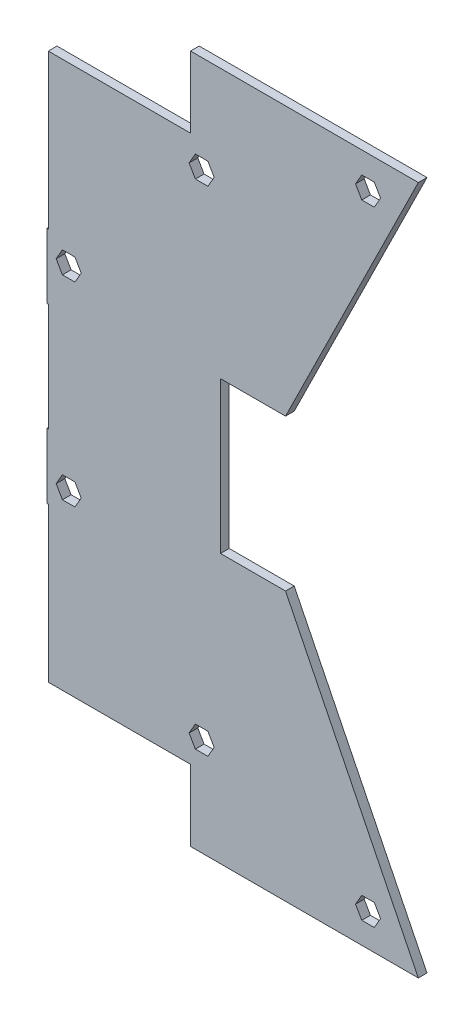
SolidWorks part; units mm, degrees
ref_plane "Front Plane" through (0, 0, 0) normal (0, 0, 1) x (1, 0, 0)
ref_plane "Top Plane" through (0, 0, 0) normal (0, 1, 0) x (1, 0, 0)
ref_plane "Right Plane" through (0, 0, 0) normal (1, 0, 0) x (0, 0, -1)
sketch "Sketch1" plane through (0, 0, 0) normal (0, 0, 1) x (1, 0, 0)
  line L0 (-2.9301, -104.5098) -> (-3.3149, -104.5098)
  line L1 (-3.3149, -72.8868) -> (-2.9301, -72.8868)
  line L54 (4.8681, -57.0118) -> (6.7012, -60.1868)
  line L55 (6.7012, -60.1868) -> (4.8681, -63.3618)
  line L56 (4.8681, -63.3618) -> (1.202, -63.3618)
  line L57 (1.202, -63.3618) -> (-0.6311, -60.1868)
  line L58 (-0.6311, -60.1868) -> (1.202, -57.0118)
  line L59 (1.202, -57.0118) -> (4.8681, -57.0118)
  line L60 (45.6227, -160.9613) -> (43.7896, -157.7863)
  line L61 (43.7896, -164.1363) -> (45.6227, -160.9613)
  line L62 (40.1235, -164.1363) -> (43.7896, -164.1363)
  line L63 (38.2904, -160.9613) -> (40.1235, -164.1363)
  line L64 (40.1235, -157.7863) -> (38.2904, -160.9613)
  line L65 (43.7896, -157.7863) -> (40.1235, -157.7863)
  line L66 (92.507, -183.1863) -> (88.8408, -183.1863)
  line L67 (92.507, -183.1863) -> (94.3401, -180.0113)
  line L68 (94.3401, -180.0113) -> (92.507, -176.8363)
  line L69 (92.507, -176.8363) -> (88.8408, -176.8363)
  line L70 (87.0077, -180.0113) -> (88.8408, -183.1863)
  line L71 (88.8408, -176.8363) -> (87.0077, -180.0113)
  line L72 (88.8408, -0.5603) -> (87.0077, 2.6147)
  line L73 (92.507, -0.5603) -> (88.8408, -0.5603)
  line L74 (94.3401, 2.6147) -> (92.507, -0.5603)
  line L75 (92.507, 5.7897) -> (94.3401, 2.6147)
  line L76 (92.507, 5.7897) -> (88.8408, 5.7897)
  line L77 (87.0077, 2.6147) -> (88.8408, 5.7897)
  line L78 (47.4851, -66.5368) -> (47.4851, -72.8868)
  line L79 (47.4851, -104.5098) -> (47.4851, -110.8598)
  line L80 (66.5174, -66.5368) -> (105.3971, 12.1397)
  line L81 (105.3971, 12.1397) -> (38.7094, 12.1397)
  line L82 (43.7896, -13.2603) -> (45.6227, -16.4353)
  line L83 (45.6227, -16.4353) -> (43.7896, -19.6103)
  line L84 (43.7896, -19.6103) -> (40.1235, -19.6103)
  line L85 (38.2904, -16.4353) -> (40.1235, -13.2603)
  line L86 (40.1235, -19.6103) -> (38.2904, -16.4353)
  line L87 (40.1235, -13.2603) -> (43.7896, -13.2603)
  line L88 (38.7094, 12.1397) -> (38.7094, -8.6883)
  line L89 (-2.9301, -8.6883) -> (38.7094, -8.6883)
  line L90 (-3.3149, -53.8368) -> (-2.9301, -53.8368)
  line L91 (-2.9301, -53.8368) -> (-2.9301, -8.6883)
  line L92 (-3.3149, -66.5368) -> (-3.3149, -53.8368)
  line L93 (-3.3149, -72.8868) -> (-3.3149, -66.5368)
  line L94 (-2.9301, -104.5098) -> (-2.9301, -72.8868)
  line L95 (-3.3149, -110.8598) -> (-3.3149, -104.5098)
  line L96 (66.5174, -110.8598) -> (105.3971, -189.5363)
  line L97 (105.3971, -189.5363) -> (38.7094, -189.5363)
  line L98 (38.7094, -189.5363) -> (38.7094, -168.7083)
  line L99 (-2.9301, -168.7083) -> (38.7094, -168.7083)
  line L100 (1.202, -120.3848) -> (4.8681, -120.3848)
  line L101 (4.8681, -120.3848) -> (6.7012, -117.2098)
  line L102 (6.7012, -117.2098) -> (4.8681, -114.0348)
  line L103 (4.8681, -114.0348) -> (1.202, -114.0348)
  line L104 (1.202, -114.0348) -> (-0.6311, -117.2098)
  line L105 (-0.6311, -117.2098) -> (1.202, -120.3848)
  line L106 (-3.3149, -110.8598) -> (-3.3149, -123.5598)
  line L107 (-3.3149, -123.5598) -> (-2.9301, -123.5598)
  line L108 (66.5174, -110.8598) -> (47.4851, -110.8598)
  line L109 (47.4851, -66.5368) -> (66.5174, -66.5368)
  line L110 (47.4851, -104.5098) -> (47.4851, -72.8868)
  line L111 (-2.9301, -123.5598) -> (-2.9301, -168.7083)
extrude "Boss-Extrude1" add sketch "Sketch1" along normal blind 2.54
